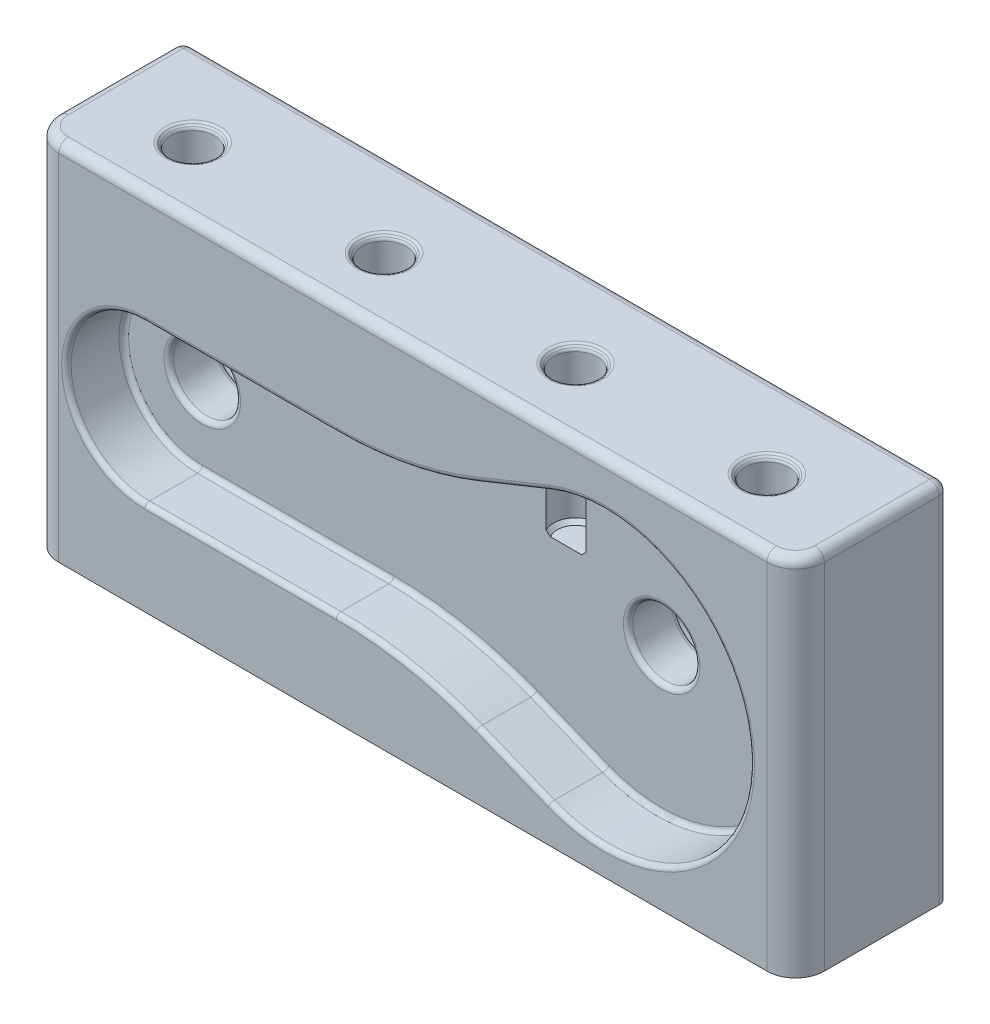
SolidWorks part; units mm, degrees
ref_plane "Front Plane" through (0, 0, 0) normal (0, 0, 1) x (1, 0, 0)
ref_plane "Top Plane" through (0, 0, 0) normal (0, 1, 0) x (1, 0, 0)
ref_plane "Right Plane" through (0, 0, 0) normal (1, 0, 0) x (0, 0, -1)
sketch "Sketch2" plane through (0, 0, 0) normal (0, 0, 1) x (1, 0, 0)
  line L1 (-20, -9.5) -> (20, -9.5)
  line L2 (-20, -9.5) -> (-20, 9.5)
  line L3 (-20, 9.5) -> (20, 9.5)
  line L4 (20, -9.5) -> (20, 9.5)
  line L5 (-20, -9.5) -> (20, 9.5) construction
  line L6 (-20, 9.5) -> (20, -9.5) construction
  point P0 (0, 0)
  dimension "D1" = 40
  dimension "D2" = 19
extrude "Boss-Extrude1" add sketch "Sketch2" along normal blind 8
fillet "Fillet1" radius 1.5 2 edges at (20, 0, 8) (-20, 0, 8)
sketch "Sketch5" plane through (0, 9.5, 0) normal (0, 1, 0) x (1, 0, 0)
  line L0 (18.5, -8) -> (-18.5, -8) construction
  line L1 (-20, -6.5) -> (-20, 0) construction
  circle A0 centre (-15, -4.5) radius 1.15
  circle A1 centre (-5, -4.5) radius 1.15
  circle A2 centre (5, -4.5) radius 1.15
  circle A3 centre (15, -4.5) radius 1.15
  dimension "D1" = 2.3
  dimension "D2" = 3.5
  dimension "D3" = 5
  dimension "D5" = 10
  dimension "D4" = 4
extrude "Cut-Extrude3" cut sketch "Sketch5" against normal blind 8
chamfer "Chamfer1" distance 0.2 angle 45 8 edges at (15, 9.5, 5.65) (15, 1.5, 5.65) (5, 9.5, 5.65) (5, 1.5, 5.65) (-5, 9.5, 5.65) (-5, 1.5, 5.65) (-15, 9.5, 5.65) (-15, 1.5, 5.65)
fillet "Fillet3" radius 0.2 8 edges at (-15, 9.3, 3.35) (-15, 9.5, 3.15) (-5, 9.3, 3.35) (-5, 9.5, 3.15) (5, 9.3, 3.35) (5, 9.5, 3.15) (15, 9.3, 3.35) (15, 9.5, 3.15)
fillet "Fillet2" radius 0.5 8 edges at (20, 9.5, 3.25) (19.5607, 9.5, 7.5607) (-20, 9.5, 3.25) (-19.5607, 9.5, 7.5607) (0, 9.5, 8) (0, 9.5, 0) (20, 0, 0) (-20, 0, 0)
sketch "Sketch6" plane through (0, 0, 8) normal (0, 0, 1) x (1, 0, 0)
  line L0 (-18.5, -9.5) -> (18.5, -9.5) construction
  line L2 (20, 9) -> (20, -9.5) construction
  circle A0 centre (-14, -0.5) radius 1.75
  circle A1 centre (10, -0.5) radius 1.75
  dimension "D1" = 3.5
  dimension "D2" = 9
  dimension "D3" = 24
  dimension "D4" = 10
extrude "Cut-Extrude4" cut sketch "Sketch6" against normal through all
sketch "Sketch7" plane through (0, 0, 0) normal (0, 0, -1) x (-1, 0, 0)
  circle A0 centre (-10, -0.5) radius 3
  circle A1 centre (14, -0.5) radius 3
  dimension "D1" = 6
extrude "Cut-Extrude5" cut sketch "Sketch7" against normal blind 2.5
sketch "Sketch8" plane through (0, 0, 8) normal (0, 0, 1) x (1, 0, 0)
  line L3 (-14, -0.5) -> (10, -0.5) construction
  line L5 (-2, -0.5) -> (-2, 8.5862) construction
  line L6 (-14, -4.6) -> (-4, -4.6)
  line L7 (-14, 3.6) -> (-4, 3.6)
  line L8 (7.1603, -7.5495) -> (3.3982, -6.0341)
  line L9 (7.1603, 6.5495) -> (3.3982, 5.0341)
  arc A5 (-14, -4.6) -> (-14, 3.6) centre (-14, -0.5) cw
  arc A6 (3.3982, 5.0341) -> (-4, 3.6) centre (-4, 23.4) cw
  arc A7 (3.3982, -6.0341) -> (-4, -4.6) centre (-4, -24.4) ccw
  arc A8 (7.1603, 6.5495) -> (7.1603, -7.5495) centre (10, -0.5) cw
  circle A9 centre (-14, -0.5) radius 1.75 construction
  circle A10 centre (10, -0.5) radius 1.75 construction
  dimension "D1" = 4.1
  dimension "D2" = 7.6
  dimension "D4" = 10
  dimension "D3" = 19.8
extrude "Cut-Extrude6" cut sketch "Sketch8" against normal blind 3
fillet "Fillet5" radius 0.25 17 edges at (-17, -0.5, 0) (7, -0.5, 0) (-17.9624, -1.5531, 5) (-9, -4.6, 5) (-0.232, -4.9618, 5) (5.2792, -6.7918, 5) (6.598, 6.323, 5) (5.2792, -6.7918, 8) (-0.232, -4.9618, 8) (-9, -4.6, 8) (-18.1, -0.5, 8) (-9, 3.6, 8) (-0.232, 3.9618, 8) (5.2792, 5.7918, 8) (16.0489, -5.1011, 5) (10.6294, 7.0739, 5) (17.6, -0.5, 8)
fillet "Fillet6" radius 0.25 4 edges at (8.25, -0.5, 5) (8.25, -0.5, 2.5) (-15.75, -0.5, 5) (-15.75, -0.5, 2.5)
